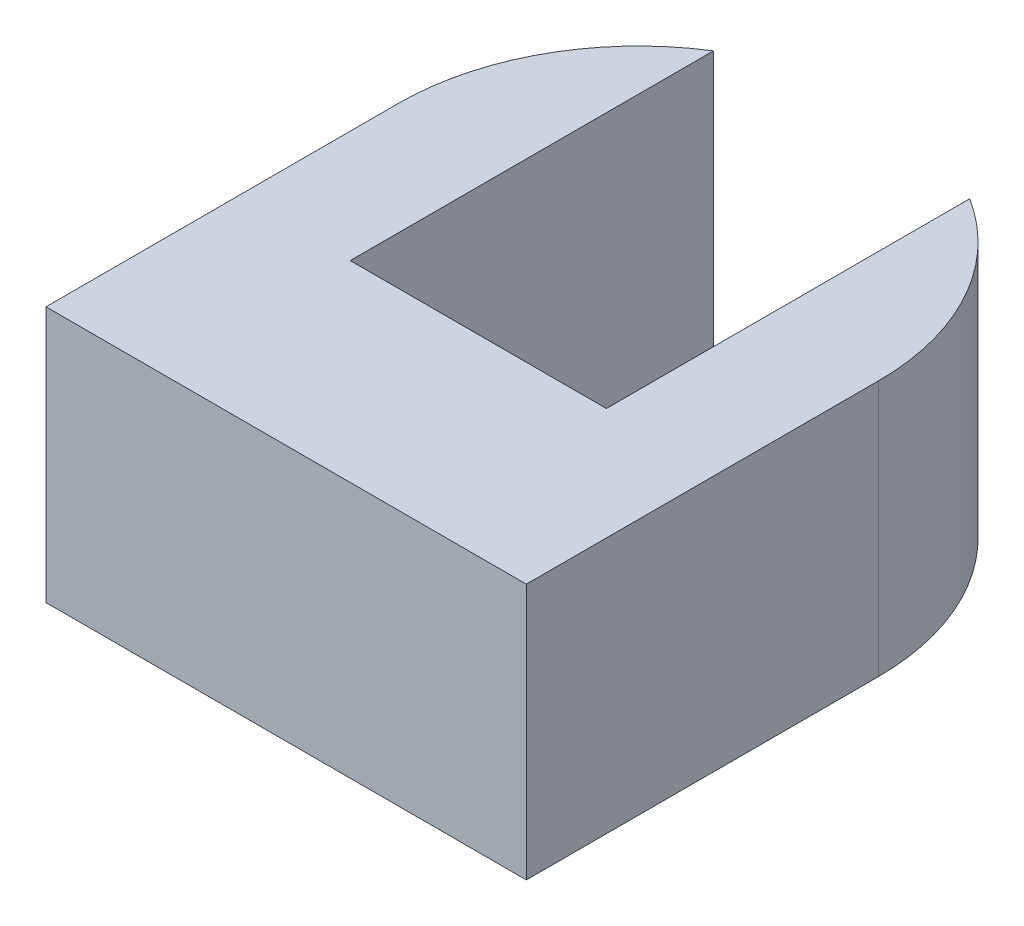
SolidWorks part; units mm, degrees
ref_plane "Front Plane" through (0, 0, 0) normal (0, 0, 1) x (1, 0, 0)
ref_plane "Top Plane" through (0, 0, 0) normal (0, 1, 0) x (1, 0, 0)
ref_plane "Right Plane" through (0, 0, 0) normal (1, 0, 0) x (0, 0, -1)
sketch "Sketch1" plane through (0, 0, 0) normal (0, 1, 0) x (1, 0, 0)
  line L0 (0, 11) -> (0, 0)
  line L1 (0, 0) -> (15, 0)
  line L2 (15, 0) -> (15, 11)
  line L3 (3.5, 17.3443) -> (3.5, 6)
  line L4 (3.5, 6) -> (11.5, 6)
  line L5 (11.5, 6) -> (11.5, 17.3443)
  line L6 (3.5, 6) -> (7.5, 11) construction
  line L7 (7.5, 11) -> (11.5, 6) construction
  arc A0 (0, 11) -> (3.5, 17.3443) centre (7.5, 11) cw
  arc A1 (15, 11) -> (11.5, 17.3443) centre (7.5, 11) ccw
  dimension "D1" = 7.5
  dimension "D2" = 8
  dimension "D3" = 6
  dimension "D4" = 5
extrude "Boss-Extrude1" add sketch "Sketch1" along normal blind 8
